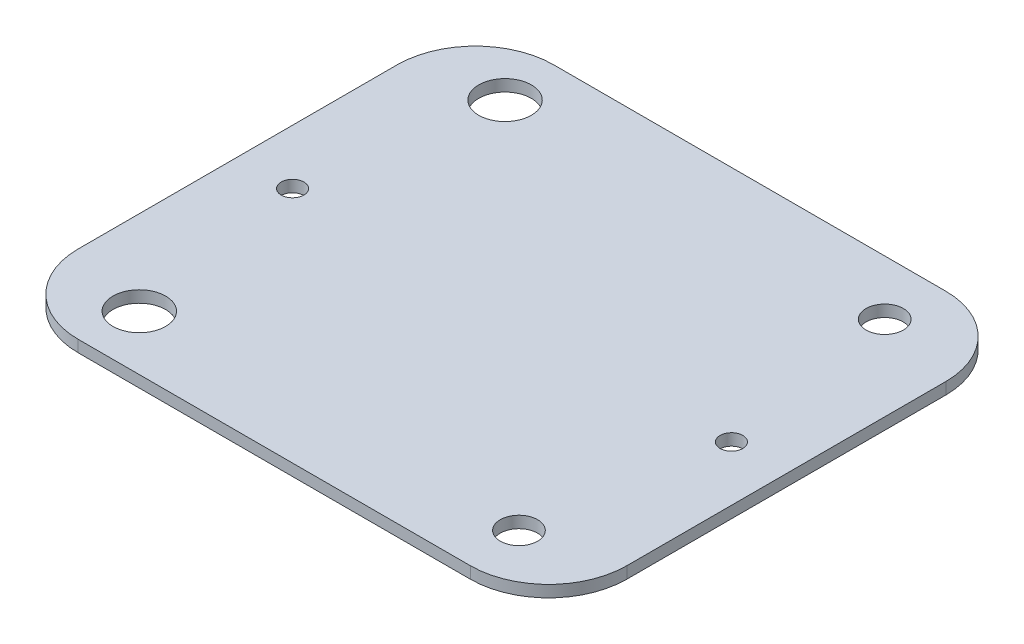
SolidWorks part; units mm, degrees
material "A-Glass Fiber"
ref_plane "Front Plane" through (0, 0, 0) normal (0, 0, 1) x (1, 0, 0)
ref_plane "Top Plane" through (0, 0, 0) normal (0, 1, 0) x (1, 0, 0)
ref_plane "Right Plane" through (0, 0, 0) normal (1, 0, 0) x (0, 0, -1)
sketch "Sketch1" plane through (0, 0, 0) normal (0, 1, 0) x (1, 0, 0)
  line L1 (-26.8, 32.5) -> (26.8, 32.5)
  line L2 (-37.5, 21.8) -> (-37.5, -21.8)
  line L3 (-26.8, -32.5) -> (26.8, -32.5)
  line L4 (37.5, 21.8) -> (37.5, -21.8)
  line L5 (-37.5, 32.5) -> (37.5, -32.5) construction
  line L6 (-37.5, -32.5) -> (37.5, 32.5) construction
  arc A0 (-37.5, -21.8) -> (-26.8, -32.5) centre (-26.8, -21.8) ccw
  arc A1 (26.8, -32.5) -> (37.5, -21.8) centre (26.8, -21.8) ccw
  arc A2 (37.5, 21.8) -> (26.8, 32.5) centre (26.8, 21.8) ccw
  arc A3 (-26.8, 32.5) -> (-37.5, 21.8) centre (-26.8, 21.8) ccw
  point P0 (0, 0)
  dimension "D3" = 10.7
  dimension "D1" = 75
  dimension "D2" = 65
extrude "Boss-Extrude1" add sketch "Sketch1" along normal blind 1.6 contours L1 A2 L4 A1 L3 A0 L2 A3
sketch "Sketch2" plane through (0, 1.6, 0) normal (0, 1, 0) x (1, 0, 0)
  line L1 (-25.95, 25) -> (25.95, 25) construction
  line L2 (-25.95, 25) -> (-25.95, -25) construction
  line L3 (-25.95, -25) -> (25.95, -25) construction
  line L4 (25.95, 25) -> (25.95, -25) construction
  line L5 (-25.95, 25) -> (25.95, -25) construction
  line L6 (-25.95, -25) -> (25.95, 25) construction
  circle A0 centre (-25.95, 25) radius 3.6
  circle A1 centre (25.95, 25) radius 2.55
  circle A2 centre (25.95, -25) radius 2.55
  circle A3 centre (-25.95, -25) radius 3.6
  point P0 (0, 0)
  dimension "D3" = 7.2
  dimension "D4" = 5.1
  dimension "D1" = 51.9
  dimension "D2" = 50
extrude "Cut-Extrude1" cut sketch "Sketch2" against normal up to surface (1.6 mm away) contours A1 | A2 | A3 | A0 up to face at (0, 0, 0)
sketch "Sketch3" plane through (0, 1.6, 0) normal (0, 1, 0) x (1, 0, 0)
  line L0 (-30, 0) -> (30, 0) construction
  circle A0 centre (-30, 0) radius 1.55
  circle A1 centre (30, 0) radius 1.55
  point P4 (0, 0)
  dimension "D2" = 3.1
  dimension "D1" = 60
extrude "Cut-Extrude2" cut sketch "Sketch3" against normal up to surface (1.6 mm away) up to face at (25.95, 0, 27.55)
